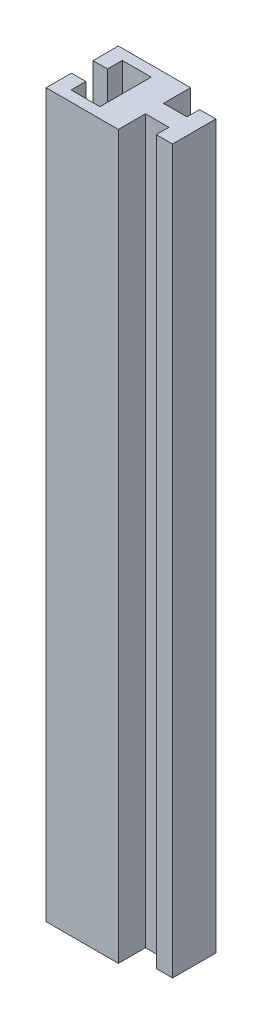
SolidWorks part; units mm, degrees
ref_plane "Front Plane" through (0, 0, 0) normal (0, 0, 1) x (1, 0, 0)
ref_plane "Top Plane" through (0, 0, 0) normal (0, 1, 0) x (1, 0, 0)
ref_plane "Right Plane" through (0, 0, 0) normal (1, 0, 0) x (0, 0, -1)
sketch "Sketch1" plane through (0, 0, 0) normal (0, 1, 0) x (1, 0, 0)
  line L1 (-31.0085, -17.4949) -> (-21.0085, -17.4949)
  line L2 (-31.0085, -17.4949) -> (-31.0085, -7.4949)
  line L3 (-31.0085, -7.4949) -> (-21.0085, -7.4949)
  line L4 (-21.0085, -17.4949) -> (-21.0085, -7.4949)
  dimension "D1" = 10
  dimension "D2" = 10
extrude "Boss-Extrude2" add sketch "Sketch1" along normal blind 100
sketch "Sketch2" plane through (0, 100, 0) normal (0, 1, 0) x (1, 0, 0)
  line L0 (-21.0085, -11.2449) -> (-17.7585, -11.2449)
  line L1 (-21.0085, -17.4949) -> (-21.0085, -7.4949) construction
  line L2 (-17.7585, -11.2449) -> (-17.7585, -9.4949)
  line L3 (-17.7585, -9.4949) -> (-15.5085, -9.4949)
  line L4 (-15.5085, -9.4949) -> (-15.5085, -15.4949)
  line L5 (-15.5085, -15.4949) -> (-17.7585, -15.4949)
  line L6 (-17.7585, -15.4949) -> (-17.7585, -13.7449)
  line L7 (-17.7585, -13.7449) -> (-21.0085, -13.7449)
  line L8 (-21.0085, -13.7449) -> (-21.0085, -11.2449)
  line L9 (-31.0085, -17.4949) -> (-21.0085, -17.4949) construction
  dimension "D1" = 6
  dimension "D2" = 1.75
  dimension "D3" = 1.75
  dimension "D4" = 3.75
  dimension "D5" = 3.25
  dimension "D6" = 2.25
  dimension "D7" = 2.25
extrude "Boss-Extrude4" add sketch "Sketch2" against normal blind 100
sketch "Sketch3" plane through (0, 100, 0) normal (0, 1, 0) x (1, 0, 0)
  line L0 (-31.0085, -13.9949) -> (-29.0085, -13.9949)
  line L1 (-29.0085, -13.9949) -> (-29.0085, -16.0449)
  line L2 (-29.0085, -16.0449) -> (-25.0085, -16.0449)
  line L3 (-25.0085, -16.0449) -> (-25.0085, -8.9449)
  line L4 (-25.0085, -8.9449) -> (-29.0085, -8.9449)
  line L5 (-29.0085, -8.9449) -> (-29.0085, -10.9949)
  line L6 (-29.0085, -10.9949) -> (-31.0085, -10.9949)
  line L7 (-31.0085, -7.4949) -> (-31.0085, -17.4949) construction
  line L8 (-31.0085, -10.9949) -> (-31.0085, -13.9949)
  line L9 (-21.0085, -7.4949) -> (-31.0085, -7.4949) construction
  dimension "D1" = 0
  dimension "D2" = 3
  dimension "D3" = 7.1
  dimension "D4" = 4
  dimension "D5" = 2.05
  dimension "D6" = 1.45
  dimension "D7" = 2
  dimension "D8" = 2
extrude "Cut-Extrude1" cut sketch "Sketch3" against normal blind 100
